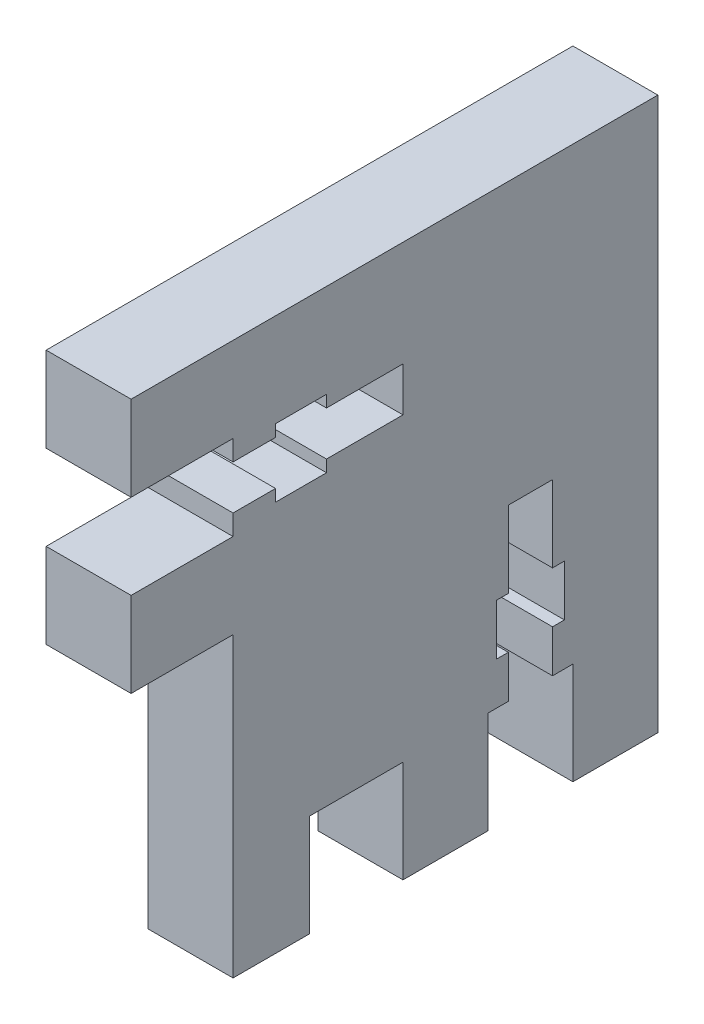
SolidWorks part; units mm, degrees
material "Acrylic (Medium-high impact)"
ref_plane "Front Plane" through (0, 0, 0) normal (0, 0, 1) x (1, 0, 0)
ref_plane "Top Plane" through (0, 0, 0) normal (0, 1, 0) x (1, 0, 0)
ref_plane "Right Plane" through (0, 0, 0) normal (1, 0, 0) x (0, 0, -1)
sketch "Sketch1" plane through (0, 0, 0) normal (1, 0, 0) x (0, 0, -1)
  line L1 (-31, -32.5) -> (31, -32.5)
  line L2 (-31, -32.5) -> (-31, 32.5)
  line L3 (-31, 32.5) -> (31, 32.5)
  line L4 (31, -32.5) -> (31, 32.5)
  line L5 (-31, -32.5) -> (31, 32.5) construction
  line L6 (-31, 32.5) -> (31, -32.5) construction
  point P0 (0, 0)
  dimension "D1" = 62
  dimension "D2" = 65
extrude "Boss-Extrude1" add sketch "Sketch1" along normal blind 10 contours L1 L4 L3 L2
sketch "Sketch2" plane through (10, 0, 0) normal (1, 0, 0) x (0, 0, -1)
  line L1 (-31, -32.5) -> (-19, -32.5)
  line L2 (-31, -32.5) -> (-31, 2.5)
  line L3 (-31, 2.5) -> (-19, 2.5)
  line L4 (-19, -32.5) -> (-19, 2.5)
  line L6 (-31, 32.5) -> (31, 32.5) construction
  line L7 (-31, -32.5) -> (-31, 32.5) construction
  line L8 (-31, -32.5) -> (31, -32.5) construction
  line L10 (18.6, -20.5) -> (21, -20.5)
  line L11 (-19, 12.5) -> (-31, 12.5)
  line L12 (-19, 12.5) -> (-19, 14.9)
  line L13 (-19, 22.5) -> (-31, 22.5)
  line L14 (-31, 12.5) -> (-31, 22.5)
  line L16 (-19, 20.1) -> (-19, 22.5)
  line L17 (1, -32.5) -> (-10, -32.5)
  line L18 (1, -32.5) -> (1, -20.5)
  line L19 (1, -20.5) -> (-10, -20.5)
  line L20 (-10, -32.5) -> (-10, -20.5)
  line L21 (11, -20.5) -> (13.4, -20.5)
  line L22 (11, -20.5) -> (11, -32.5)
  line L23 (11, -32.5) -> (21, -32.5)
  line L24 (21, -20.5) -> (21, -32.5)
  line L25 (-19, 20.1) -> (-14, 20.1)
  line L26 (-14, 14.9) -> (-14, 13.5)
  line L27 (-19, 14.9) -> (-14, 14.9)
  line L28 (1, 20.1) -> (1, 14.9)
  line L29 (-14, 21.5) -> (-8, 21.5)
  line L30 (-14, 21.5) -> (-14, 20.1)
  line L31 (-14, 13.5) -> (-8, 13.5)
  line L32 (-8, 21.5) -> (-8, 20.1)
  line L33 (-8, 20.1) -> (1, 20.1)
  line L34 (-8, 14.9) -> (-8, 13.5)
  line L35 (-8, 14.9) -> (1, 14.9)
  line L36 (18.6, -15.5) -> (20, -15.5)
  line L37 (13.4, -9.5) -> (13.4, -0.5)
  line L38 (13.4, -20.5) -> (13.4, -15.5)
  line L39 (13.4, -0.5) -> (18.6, -0.5)
  line L40 (18.6, -20.5) -> (18.6, -15.5)
  line L41 (12, -9.5) -> (13.4, -9.5)
  line L42 (12, -9.5) -> (12, -15.5)
  line L43 (12, -15.5) -> (13.4, -15.5)
  line L44 (20, -9.5) -> (20, -15.5)
  line L45 (18.6, -9.5) -> (20, -9.5)
  line L46 (18.6, -9.5) -> (18.6, -0.5)
  dimension "D2" = 35
  dimension "D3" = 12
  dimension "D4" = 10
  dimension "D6" = 12
  dimension "D7" = 10
  dimension "D9" = 9
  dimension "D10" = 11
  dimension "D11" = 10
  dimension "D12" = 10
  dimension "D13" = 1
  dimension "D14" = 8
  dimension "D15" = 6
  dimension "D16" = 20
  dimension "D17" = 5.2
  dimension "D18" = 1.4
  dimension "D19" = 5
  dimension "D20" = 5.2
  dimension "D21" = 1.4
  dimension "D22" = 1
  dimension "D23" = 5
  dimension "D24" = 6
  dimension "D25" = 8
  dimension "D26" = 20
  dimension "D27" = 12
extrude "Cut-Extrude2" cut sketch "Sketch2" against normal through all
